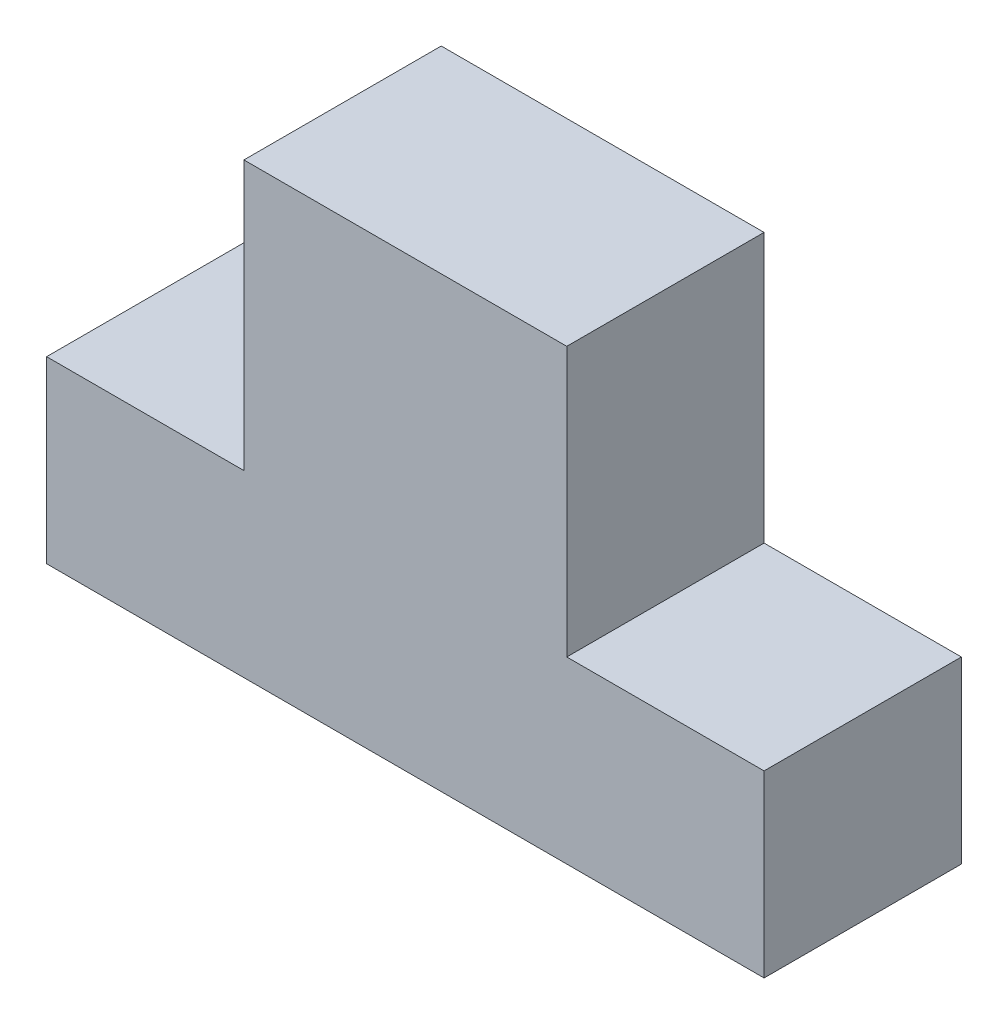
SolidWorks part; units mm, degrees
material "ﾁｰｸ材"
ref_plane "正面" through (0, 0, 0) normal (0, 0, 1) x (1, 0, 0)
ref_plane "平面" through (0, 0, 0) normal (0, 1, 0) x (1, 0, 0)
ref_plane "右側面" through (0, 0, 0) normal (1, 0, 0) x (0, 0, -1)
sketch "ｽｹｯﾁ1" plane through (0, 0, 0) normal (0, 0, 1) x (1, 0, 0)
  line L0 (-10, 0) -> (10, 0)
  line L1 (10, 0) -> (10, 5)
  line L2 (10, 5) -> (4.5, 5)
  line L3 (4.5, 5) -> (4.5, 12.5)
  line L4 (4.5, 12.5) -> (-4.5, 12.5)
  line L5 (-4.5, 12.5) -> (-4.5, 5)
  line L6 (-4.5, 5) -> (-10, 5)
  line L7 (-10, 5) -> (-10, 0)
  dimension "D1" = 5
  dimension "D2" = 5.5
  dimension "D3" = 5.5
  dimension "D4" = 7.5
  dimension "D5" = 20
extrude "ﾎﾞｽ - 押し出し1" add sketch "ｽｹｯﾁ1" along normal blind 5.5
